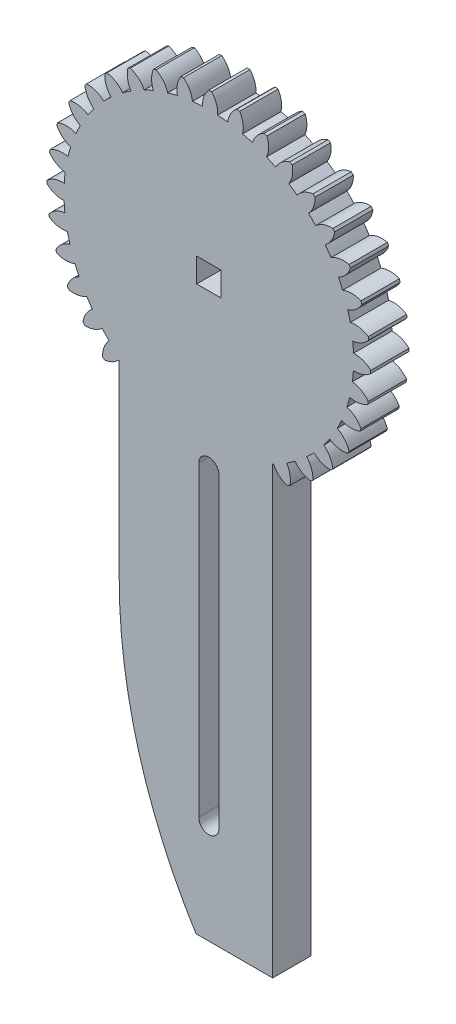
SolidWorks part; units mm, degrees
ref_plane "Front Plane" through (0, 0, 0) normal (0, 0, 1) x (1, 0, 0)
ref_plane "Top Plane" through (0, 0, 0) normal (0, 1, 0) x (1, 0, 0)
ref_plane "Right Plane" through (0, 0, 0) normal (1, 0, 0) x (0, 0, -1)
sketch "Sketch3" plane through (0, 0, 0) normal (0, 0, 1) x (1, 0, 0)
  line L1 (-1.5, -1.5) -> (1.5, -1.5)
  line L2 (-1.5, -1.5) -> (-1.5, 1.5)
  line L3 (-1.5, 1.5) -> (1.5, 1.5)
  line L4 (1.5, -1.5) -> (1.5, 1.5)
  line L5 (-1.5, -1.5) -> (1.5, 1.5) construction
  line L6 (-1.5, 1.5) -> (1.5, -1.5) construction
  line L10 (-1.6002, -71.4248) -> (7.9248, -71.4248)
  line L11 (7.9248, -12.7) -> (7.9248, -71.4248)
  line L13 (-11.1252, -12.7) -> (-11.1252, -38.1)
  line L14 (0, 0) -> (0, -12.7) construction
  line L16 (7.9248, -12.7) -> (-11.1252, -12.7)
  arc A0 (-11.1252, -38.1) -> (-1.6002, -71.4248) centre (51.9335, -38.1) ccw
  point P0 (0, 0)
  arc B0 (-17.1536, 5.4085) -> (-17.489, 4.1987) centre (0, 0) ccw
  arc B1 (-17.8704, -2.0361) -> (-19.8566, -3.145) centre (-17.5364, -4.9676) ccw
  arc B2 (-19.7987, -3.491) -> (-17.5597, -3.8929) centre (-18.1983, -1.0124) ccw
  arc B3 (-17.5597, -3.8929) -> (-17.2453, -5.1083) centre (0, 0) ccw
  arc B4 (-17.9525, 1.098) -> (-20.101, 0.3509) centre (-18.1326, -1.8469) ccw
  arc B5 (-17.8321, 2.3476) -> (-17.9525, 1.098) centre (0, 0) ccw
  arc B6 (-17.489, 4.1987) -> (-19.7347, 3.836) centre (-18.1778, 1.3298) ccw
  arc B7 (-19.7987, 3.491) -> (-17.8321, 2.3476) centre (-17.447, 5.2728) ccw
  arc B8 (-18.8917, 6.876) -> (-17.1536, 5.4085) centre (-16.2663, 8.2224) ccw
  arc B9 (-14.2693, 10.9492) -> (-14.9983, 9.9271) centre (0, 0) ccw
  arc B10 (-15.4006, 12.9227) -> (-14.2693, 10.9492) centre (-12.4731, 13.2899) ccw
  arc B11 (-15.1728, 13.1895) -> (-15.4006, 12.9227) centre (0, 0) ccw
  arc B12 (-13.0466, 12.3807) -> (-15.1728, 13.1895) centre (-15.0775, 10.2406) ccw
  arc B13 (-12.1512, 13.2607) -> (-13.0466, 12.3807) centre (0, 0) ccw
  arc B14 (-12.9227, 15.4006) -> (-12.1512, 13.2607) centre (-9.9759, 15.254) ccw
  arc B15 (-12.6519, 15.6238) -> (-12.9227, 15.4006) centre (0, 0) ccw
  arc B16 (-10.6985, 14.4582) -> (-12.6519, 15.6238) centre (-13.0702, 12.7032) ccw
  arc B17 (-9.6639, 15.1692) -> (-10.6985, 14.4582) centre (0, 0) ccw
  arc B18 (-10.0521, 17.4107) -> (-9.6639, 15.1692) centre (-7.1755, 16.7545) ccw
  arc B19 (-9.7467, 17.5834) -> (-10.0521, 17.4107) centre (0, 0) ccw
  arc B20 (-8.0253, 16.0963) -> (-9.7467, 17.5834) centre (-10.6658, 14.7798) ccw
  arc B21 (-6.8829, 16.6169) -> (-8.0253, 16.0963) centre (0, 0) ccw
  arc B22 (-6.876, 18.8917) -> (-6.8829, 16.6169) centre (-4.1571, 17.746) ccw
  arc B23 (-6.5453, 19.0088) -> (-6.876, 18.8917) centre (0, 0) ccw
  arc B24 (-5.1083, 17.2453) -> (-6.5453, 19.0088) centre (-7.9372, 16.4074) ccw
  arc B25 (-3.8929, 17.5597) -> (-5.1083, 17.2453) centre (0, 0) ccw
  arc B26 (-3.491, 19.7987) -> (-3.8929, 17.5597) centre (-1.0124, 18.1983) ccw
  arc B27 (-3.145, 19.8566) -> (-3.491, 19.7987) centre (0, 0) ccw
  arc B28 (-2.0361, 17.8704) -> (-3.145, 19.8566) centre (-4.9676, 17.5364) ccw
  arc B29 (-0.7845, 17.9689) -> (-2.0361, 17.8704) centre (0, 0) ccw
  arc B30 (0, 20.1041) -> (-0.7845, 17.9689) centre (2.1631, 18.0976) ccw
  arc B31 (0.3509, 20.101) -> (0, 20.1041) centre (0, 0) ccw
  arc B32 (1.098, 17.9525) -> (0.3509, 20.101) centre (-1.8469, 18.1326) ccw
  arc B33 (2.3476, 17.8321) -> (1.098, 17.9525) centre (0, 0) ccw
  arc B34 (3.491, 19.7987) -> (2.3476, 17.8321) centre (5.2728, 17.447) ccw
  arc B35 (3.836, 19.7347) -> (3.491, 19.7987) centre (0, 0) ccw
  arc B36 (4.1987, 17.489) -> (3.836, 19.7347) centre (1.3298, 18.1778) ccw
  arc B37 (5.4085, 17.1536) -> (4.1987, 17.489) centre (0, 0) ccw
  arc B38 (6.876, 18.8917) -> (5.4085, 17.1536) centre (8.2224, 16.2663) ccw
  arc B39 (7.2047, 18.7688) -> (6.876, 18.8917) centre (0, 0) ccw
  arc B40 (7.1719, 16.4942) -> (7.2047, 18.7688) centre (4.4662, 17.6707) ccw
  arc B41 (8.305, 15.9538) -> (7.1719, 16.4942) centre (0, 0) ccw
  arc B42 (10.052, 17.4107) -> (8.305, 15.9538) centre (10.9221, 14.5914) ccw
  arc B43 (10.3544, 17.2326) -> (10.052, 17.4107) centre (0, 0) ccw
  arc B44 (9.9271, 14.9983) -> (10.3544, 17.2326) centre (7.4668, 16.6267) ccw
  arc B45 (10.9492, 14.2693) -> (9.9271, 14.9983) centre (0, 0) ccw
  arc B46 (12.9227, 15.4006) -> (10.9492, 14.2693) centre (13.2899, 12.4731) ccw
  arc B47 (13.1895, 15.1728) -> (12.9227, 15.4006) centre (0, 0) ccw
  arc B48 (12.3807, 13.0466) -> (13.1895, 15.1728) centre (10.2406, 15.0775) ccw
  arc B49 (13.2607, 12.1512) -> (12.3807, 13.0466) centre (0, 0) ccw
  arc B50 (15.4006, 12.9227) -> (13.2607, 12.1512) centre (15.254, 9.9759) ccw
  arc B51 (15.6238, 12.6519) -> (15.4006, 12.9227) centre (0, 0) ccw
  arc B52 (14.4582, 10.6985) -> (15.6238, 12.6519) centre (12.7032, 13.0702) ccw
  arc B53 (15.1692, 9.6639) -> (14.4582, 10.6985) centre (0, 0) ccw
  arc B54 (17.4107, 10.0521) -> (15.1692, 9.6639) centre (16.7545, 7.1755) ccw
  arc B55 (17.5834, 9.7467) -> (17.4107, 10.0521) centre (0, 0) ccw
  arc B56 (16.0963, 8.0253) -> (17.5834, 9.7467) centre (14.7798, 10.6658) ccw
  arc B57 (16.6169, 6.8829) -> (16.0963, 8.0253) centre (0, 0) ccw
  arc B58 (18.8917, 6.876) -> (16.6169, 6.8829) centre (17.746, 4.1571) ccw
  arc B59 (19.0088, 6.5453) -> (18.8917, 6.876) centre (0, 0) ccw
  arc B60 (17.2453, 5.1083) -> (19.0088, 6.5453) centre (16.4074, 7.9372) ccw
  arc B61 (17.5597, 3.8929) -> (17.2453, 5.1083) centre (0, 0) ccw
  arc B62 (19.7987, 3.491) -> (17.5597, 3.8929) centre (18.1983, 1.0124) ccw
  arc B63 (19.8566, 3.145) -> (19.7987, 3.491) centre (0, 0) ccw
  arc B64 (17.8704, 2.0361) -> (19.8566, 3.145) centre (17.5364, 4.9676) ccw
  arc B65 (17.9689, 0.7845) -> (17.8704, 2.0361) centre (0, 0) ccw
  arc B66 (20.1041, 0) -> (17.9689, 0.7845) centre (18.0976, -2.1631) ccw
  arc B67 (20.101, -0.3509) -> (20.1041, 0) centre (0, 0) ccw
  arc B68 (17.9525, -1.098) -> (20.101, -0.3509) centre (18.1326, 1.8469) ccw
  arc B69 (17.8321, -2.3476) -> (17.9525, -1.098) centre (0, 0) ccw
  arc B70 (19.7987, -3.491) -> (17.8321, -2.3476) centre (17.447, -5.2728) ccw
  arc B71 (19.7347, -3.836) -> (19.7987, -3.491) centre (0, 0) ccw
  arc B72 (17.489, -4.1987) -> (19.7347, -3.836) centre (18.1778, -1.3298) ccw
  arc B73 (17.1536, -5.4085) -> (17.489, -4.1987) centre (0, 0) ccw
  arc B74 (18.8917, -6.876) -> (17.1536, -5.4085) centre (16.2663, -8.2224) ccw
  arc B75 (18.7688, -7.2047) -> (18.8917, -6.876) centre (0, 0) ccw
  arc B76 (16.4942, -7.1719) -> (18.7688, -7.2047) centre (17.6707, -4.4662) ccw
  arc B77 (15.9538, -8.305) -> (16.4942, -7.1719) centre (0, 0) ccw
  arc B78 (17.4107, -10.052) -> (15.9538, -8.305) centre (14.5914, -10.9221) ccw
  arc B79 (17.2326, -10.3544) -> (17.4107, -10.052) centre (0, 0) ccw
  arc B80 (14.9983, -9.9271) -> (17.2326, -10.3544) centre (16.6267, -7.4668) ccw
  arc B81 (14.2693, -10.9492) -> (14.9983, -9.9271) centre (0, 0) ccw
  arc B82 (15.4006, -12.9227) -> (14.2693, -10.9492) centre (12.4731, -13.2899) ccw
  arc B83 (15.1728, -13.1895) -> (15.4006, -12.9227) centre (0, 0) ccw
  arc B84 (13.0466, -12.3807) -> (15.1728, -13.1895) centre (15.0775, -10.2406) ccw
  arc B85 (12.1512, -13.2607) -> (13.0466, -12.3807) centre (0, 0) ccw
  arc B86 (12.9227, -15.4006) -> (12.1512, -13.2607) centre (9.9759, -15.254) ccw
  arc B87 (12.6519, -15.6238) -> (12.9227, -15.4006) centre (0, 0) ccw
  arc B88 (10.6985, -14.4582) -> (12.6519, -15.6238) centre (13.0702, -12.7032) ccw
  arc B89 (9.6639, -15.1692) -> (10.6985, -14.4582) centre (0, 0) ccw
  arc B90 (10.0521, -17.4107) -> (9.6639, -15.1692) centre (7.1755, -16.7545) ccw
  arc B91 (9.7467, -17.5834) -> (10.0521, -17.4107) centre (0, 0) ccw
  arc B92 (8.0253, -16.0963) -> (9.7467, -17.5834) centre (10.6658, -14.7798) ccw
  arc B93 (6.8829, -16.6169) -> (8.0253, -16.0963) centre (0, 0) ccw
  arc B94 (6.876, -18.8917) -> (6.8829, -16.6169) centre (4.1571, -17.746) ccw
  arc B95 (6.5453, -19.0088) -> (6.876, -18.8917) centre (0, 0) ccw
  arc B96 (5.1083, -17.2453) -> (6.5453, -19.0088) centre (7.9372, -16.4074) ccw
  arc B97 (3.8929, -17.5597) -> (5.1083, -17.2453) centre (0, 0) ccw
  arc B98 (3.491, -19.7987) -> (3.8929, -17.5597) centre (1.0124, -18.1983) ccw
  arc B99 (3.145, -19.8566) -> (3.491, -19.7987) centre (0, 0) ccw
  arc B100 (2.0361, -17.8704) -> (3.145, -19.8566) centre (4.9676, -17.5364) ccw
  arc B101 (0.7845, -17.9689) -> (2.0361, -17.8704) centre (0, 0) ccw
  arc B102 (0, -20.1041) -> (0.7845, -17.9689) centre (-2.1631, -18.0976) ccw
  arc B103 (-0.3509, -20.101) -> (0, -20.1041) centre (0, 0) ccw
  arc B104 (-1.098, -17.9525) -> (-0.3509, -20.101) centre (1.8469, -18.1326) ccw
  arc B105 (-2.3476, -17.8321) -> (-1.098, -17.9525) centre (0, 0) ccw
  arc B106 (-3.491, -19.7987) -> (-2.3476, -17.8321) centre (-5.2728, -17.447) ccw
  arc B107 (-3.836, -19.7347) -> (-3.491, -19.7987) centre (0, 0) ccw
  arc B108 (-4.1987, -17.489) -> (-3.836, -19.7347) centre (-1.3298, -18.1778) ccw
  arc B109 (-5.4085, -17.1536) -> (-4.1987, -17.489) centre (0, 0) ccw
  arc B110 (-6.876, -18.8917) -> (-5.4085, -17.1536) centre (-8.2224, -16.2663) ccw
  arc B111 (-7.2047, -18.7688) -> (-6.876, -18.8917) centre (0, 0) ccw
  arc B112 (-7.1719, -16.4942) -> (-7.2047, -18.7688) centre (-4.4662, -17.6707) ccw
  arc B113 (-8.305, -15.9538) -> (-7.1719, -16.4942) centre (0, 0) ccw
  arc B114 (-10.052, -17.4107) -> (-8.305, -15.9538) centre (-10.9221, -14.5914) ccw
  arc B115 (-10.3544, -17.2326) -> (-10.052, -17.4107) centre (0, 0) ccw
  arc B116 (-9.9271, -14.9983) -> (-10.3544, -17.2326) centre (-7.4668, -16.6267) ccw
  arc B117 (-10.9492, -14.2693) -> (-9.9271, -14.9983) centre (0, 0) ccw
  arc B118 (-12.9227, -15.4006) -> (-10.9492, -14.2693) centre (-13.2899, -12.4731) ccw
  arc B119 (-13.1895, -15.1728) -> (-12.9227, -15.4006) centre (0, 0) ccw
  arc B120 (-12.3807, -13.0466) -> (-13.1895, -15.1728) centre (-10.2406, -15.0775) ccw
  arc B121 (-13.2607, -12.1512) -> (-12.3807, -13.0466) centre (0, 0) ccw
  arc B122 (-15.4006, -12.9227) -> (-13.2607, -12.1512) centre (-15.254, -9.9759) ccw
  arc B123 (-15.6238, -12.6519) -> (-15.4006, -12.9227) centre (0, 0) ccw
  arc B124 (-14.4582, -10.6985) -> (-15.6238, -12.6519) centre (-12.7032, -13.0702) ccw
  arc B125 (-15.1692, -9.6639) -> (-14.4582, -10.6985) centre (0, 0) ccw
  arc B126 (-17.4107, -10.0521) -> (-15.1692, -9.6639) centre (-16.7545, -7.1755) ccw
  arc B127 (-17.5834, -9.7467) -> (-17.4107, -10.0521) centre (0, 0) ccw
  arc B128 (-16.0963, -8.0253) -> (-17.5834, -9.7467) centre (-14.7798, -10.6658) ccw
  arc B129 (-16.6169, -6.8829) -> (-16.0963, -8.0253) centre (0, 0) ccw
  arc B130 (-18.8917, -6.876) -> (-16.6169, -6.8829) centre (-17.746, -4.1571) ccw
  arc B131 (-19.0088, -6.5453) -> (-18.8917, -6.876) centre (0, 0) ccw
  arc B132 (-17.2453, -5.1083) -> (-19.0088, -6.5453) centre (-16.4074, -7.9372) ccw
  arc B133 (-19.8566, -3.145) -> (-19.7987, -3.491) centre (0, 0) ccw
  arc B134 (-17.9689, -0.7845) -> (-17.8704, -2.0361) centre (0, 0) ccw
  arc B135 (-20.1041, 0) -> (-17.9689, -0.7845) centre (-18.0976, 2.1631) ccw
  arc B136 (-20.101, 0.3509) -> (-20.1041, 0) centre (0, 0) ccw
  arc B137 (-19.7347, 3.836) -> (-19.7987, 3.491) centre (0, 0) ccw
  arc B138 (-18.7688, 7.2047) -> (-18.8917, 6.876) centre (0, 0) ccw
  arc B139 (-16.4942, 7.1719) -> (-18.7688, 7.2047) centre (-17.6707, 4.4662) ccw
  arc B140 (-15.9538, 8.305) -> (-16.4942, 7.1719) centre (0, 0) ccw
  arc B141 (-17.4107, 10.052) -> (-15.9538, 8.305) centre (-14.5914, 10.9221) ccw
  arc B142 (-17.2326, 10.3544) -> (-17.4107, 10.052) centre (0, 0) ccw
  arc B143 (-14.9983, 9.9271) -> (-17.2326, 10.3544) centre (-16.6267, 7.4668) ccw
sketch_block_instance "VEX-36-TOOTH-GEAR-b-1"
sketch_block "VEX-36-TOOTH-GEAR-b"
other "DetailItem3"
other "DetailItem4" parameters "D3"=5.08, "D2"=55.88, "D1"=3.0671, "D4"=36.7485, "D5"=18.9201, "D6"=63.0103, "D7"=9.525
extrude "Boss-Extrude2" add sketch "Sketch3" along normal blind 4.7625
sketch "Sketch4" plane through (0, 0, 4.7625) normal (0, 0, 1) x (1, 0, 0)
  circle A0 centre (0, 0) radius 2.1213
sketch "Sketch5" plane through (0, 0, 4.7625) normal (0, 0, 1) x (1, 0, 0)
  line L0 (0, -58.7248) -> (0, -20.6248) construction
  line L1 (-1.25, -58.7248) -> (-1.25, -20.6248)
  line L2 (1.25, -58.7248) -> (1.25, -20.6248)
  line L3 (-1.6002, -71.4248) -> (7.9248, -71.4248) construction
  arc A0 (-1.25, -58.7248) -> (1.25, -58.7248) centre (0, -58.7248) ccw
  arc A1 (1.25, -20.6248) -> (-1.25, -20.6248) centre (0, -20.6248) ccw
  point P3 (0, -39.6748)
  dimension "D1" = 2.5
  dimension "D2" = 12.7
  dimension "D3" = 38.1
extrude "Cut-Extrude1" cut sketch "Sketch5" against normal blind 10.16
